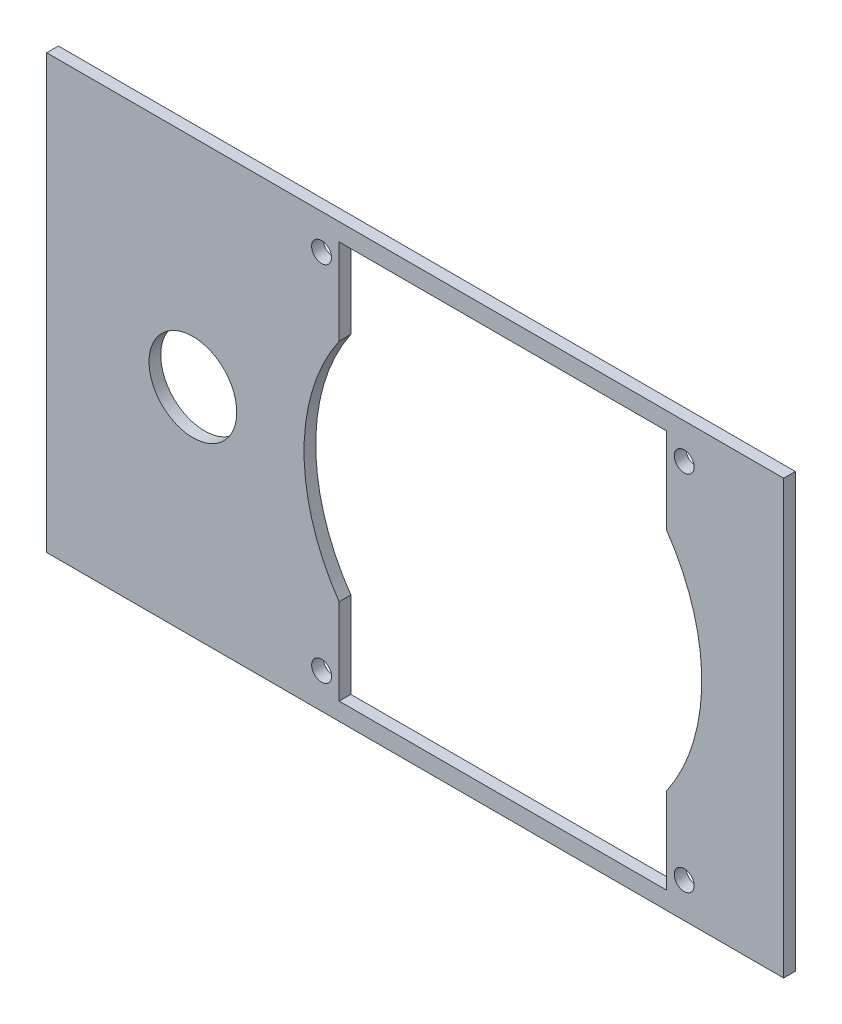
SolidWorks part; units mm, degrees
ref_plane "Plano frontal" through (0, 0, 0) normal (0, 0, 1) x (1, 0, 0)
ref_plane "Plano superior" through (0, 0, 0) normal (0, 1, 0) x (1, 0, 0)
ref_plane "Plano direito" through (0, 0, 0) normal (1, 0, 0) x (0, 0, -1)
sketch "Esboço1" plane through (0, 0, 0) normal (0, 0, 1) x (1, 0, 0)
  line L0 (0, 0) -> (126, 0)
  line L1 (50, -3) -> (50, -17.7127)
  line L2 (126, -74) -> (0, -74)
  line L3 (0, -74) -> (0, 0)
  line L4 (47, -6) -> (109, -6) construction
  line L5 (50, -71) -> (106, -71)
  line L6 (126, 0) -> (126, -74)
  line L7 (50, -56.2873) -> (50, -71)
  line L8 (106, -3) -> (106, -17.7127)
  line L9 (106, -56.2873) -> (106, -71)
  line L10 (47, -6) -> (109, -68) construction
  line L11 (109, -6) -> (109, -68) construction
  line L13 (50, -3) -> (106, -3)
  circle A0 centre (47, -6) radius 1.7
  circle A1 centre (109, -6) radius 1.7
  circle A2 centre (47, -68) radius 1.7
  circle A3 centre (109, -68) radius 1.7
  arc A4 (50, -17.7127) -> (50, -56.2873) centre (78, -37) ccw
  arc A5 (106, -56.2873) -> (106, -17.7127) centre (78, -37) ccw
  circle A6 centre (25, -37) radius 7.5
  point P13 (78, -6)
  point P23 (78, -3)
  point P26 (0, -37)
  point P27 (0, 0)
  dimension "D4" = 3.4
  dimension "D10" = 15
  dimension "D1" = 20
  dimension "D2" = 56
  dimension "D3" = 62
  dimension "D5" = 126
  dimension "D6" = 74
  dimension "D7" = 3
  dimension "D8" = 3
  dimension "D9" = 6
  dimension "D11" = 25
extrude "Ressalto-extrusão1" add sketch "Esboço1" along normal blind 2
